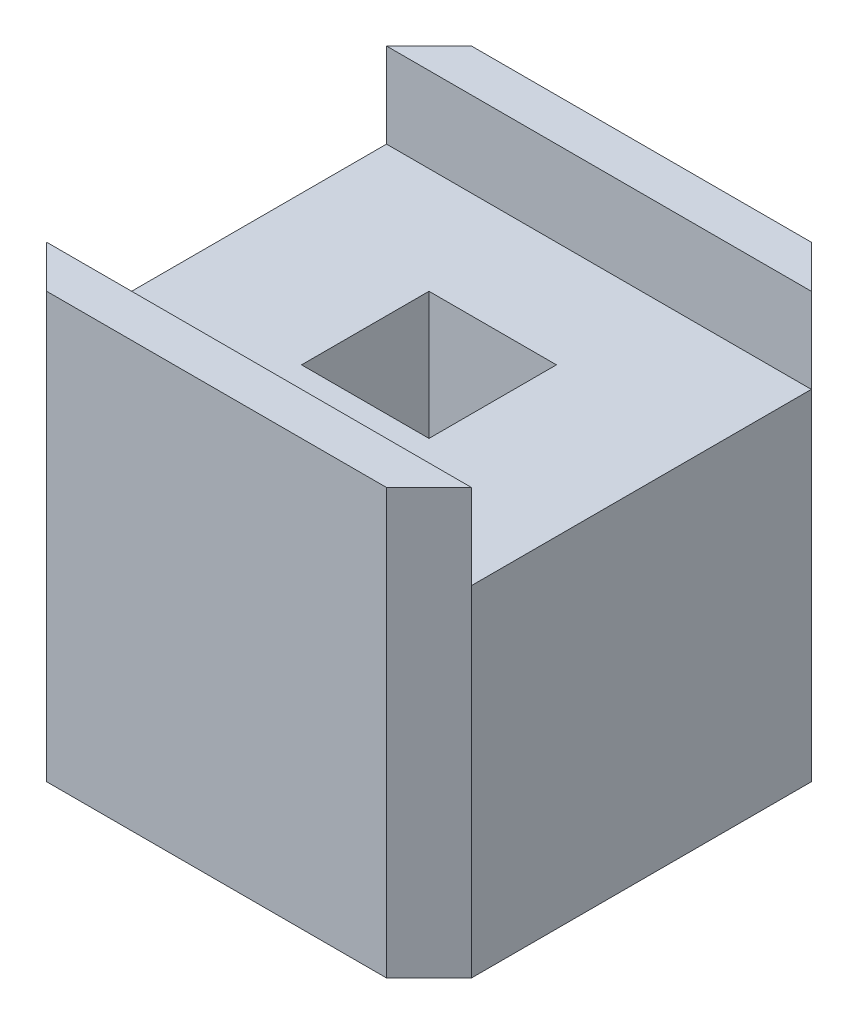
SolidWorks part; units mm, degrees
ref_plane "Front Plane" through (0, 0, 0) normal (0, 0, 1) x (1, 0, 0)
ref_plane "Top Plane" through (0, 0, 0) normal (0, 1, 0) x (1, 0, 0)
ref_plane "Right Plane" through (0, 0, 0) normal (1, 0, 0) x (0, 0, -1)
sketch "Sketch1" plane through (0, 0, 0) normal (0, 1, 0) x (1, 0, 0)
  line L0 (-1.25, 1) -> (-1, 1.25)
  line L1 (-1, 1.25) -> (1, 1.25)
  line L2 (-1.25, 1) -> (-1.25, -1)
  line L3 (-1, -1.25) -> (1, -1.25)
  line L4 (1.25, 1) -> (1.25, -1)
  line L5 (-1.25, 1.25) -> (1.25, -1.25) construction
  line L6 (-1.25, -1.25) -> (1.25, 1.25) construction
  line L7 (-0.375, 0.375) -> (0.375, 0.375)
  line L8 (-0.375, 0.375) -> (-0.375, -0.375)
  line L9 (-0.375, -0.375) -> (0.375, -0.375)
  line L10 (0.375, 0.375) -> (0.375, -0.375)
  line L11 (-0.375, 0.375) -> (0.375, -0.375) construction
  line L12 (-0.375, -0.375) -> (0.375, 0.375) construction
  line L13 (1, 1.25) -> (1.25, 1)
  line L14 (1, -1.25) -> (1.25, -1)
  line L15 (-1.25, -1) -> (-1, -1.25)
  point P0 (0, 0)
  point P6 (0, 0)
  dimension "D1" = 2.5
  dimension "D2" = 2.5
  dimension "D3" = 0.75
extrude "Boss-Extrude1" add sketch "Sketch1" along normal blind 2.5
sketch "Sketch2" plane through (0, 2.5, 0) normal (0, 1, 0) x (1, 0, 0)
  line L1 (-1.25, 1) -> (1.25, 1)
  line L2 (-1.25, 1) -> (-1.25, -1)
  line L3 (-1.25, -1) -> (1.25, -1)
  line L4 (1.25, 1) -> (1.25, -1)
extrude "Cut-Extrude1" cut sketch "Sketch2" against normal blind 0.5
